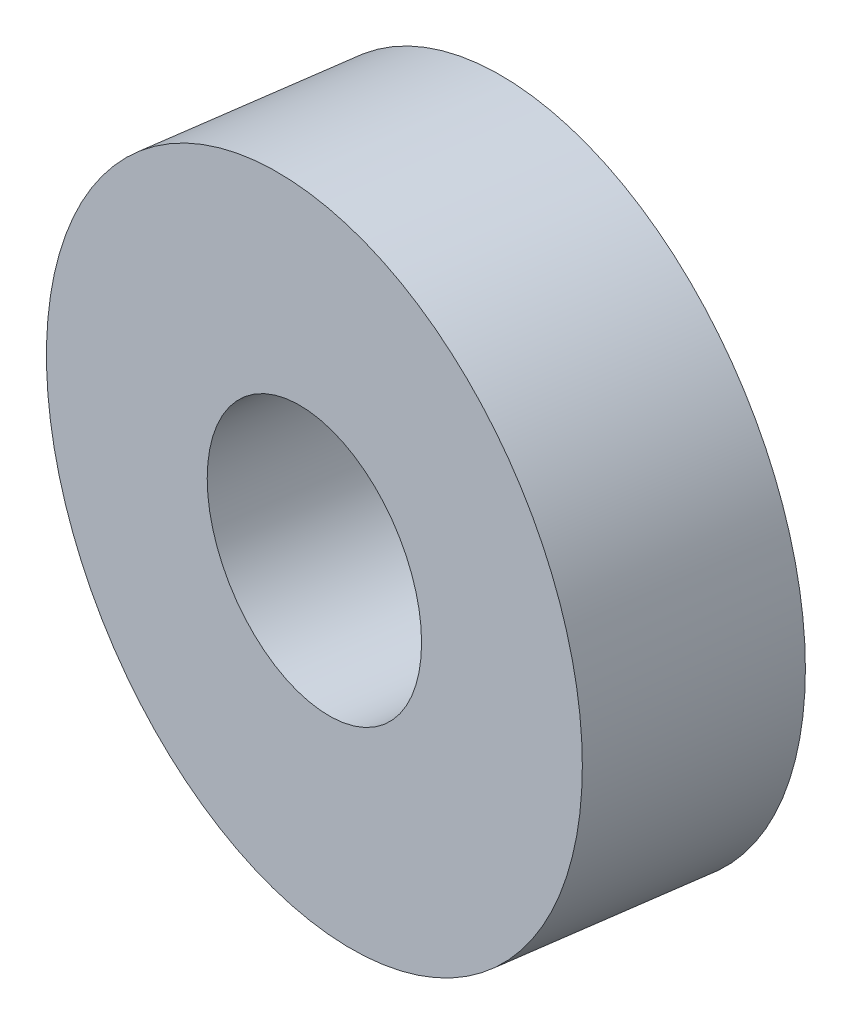
SolidWorks part; units mm, degrees
ref_plane "Front Plane" through (0, 0, 0) normal (0, 0, 1) x (1, 0, 0)
ref_plane "Top Plane" through (0, 0, 0) normal (0, 1, 0) x (1, 0, 0)
ref_plane "Right Plane" through (0, 0, 0) normal (1, 0, 0) x (0, 0, -1)
sketch "Sketch1" plane through (-29.4736, 0, 32.5552) normal (0.9903, 0, 0.1393) x (0.1393, 0, -0.9903)
  line L0 (22.0768, -11.1359) -> (73.3766, -11.1359) construction
  line L1 (38.8875, -14.3109) -> (56.5659, -14.3109) construction
  line L2 (45.2375, -19.0734) -> (50.2159, -19.0734) construction
  line L3 (50.2159, -3.1984) -> (50.2159, -19.0734) construction
  line L4 (45.2375, -3.1984) -> (45.2375, -19.0734) construction
  line L5 (45.2375, -11.1359) -> (50.2159, -11.1359)
  line L7 (45.2375, -19.0734) -> (50.2159, -19.0734)
  line L8 (50.2159, -14.3109) -> (50.2159, -19.0734)
  line L9 (45.2375, -14.3109) -> (45.2375, -19.0734)
  line L11 (45.2375, -14.3109) -> (50.2159, -14.3109)
revolve "Revolve1" add sketch "Sketch1" angle 360 about L5
